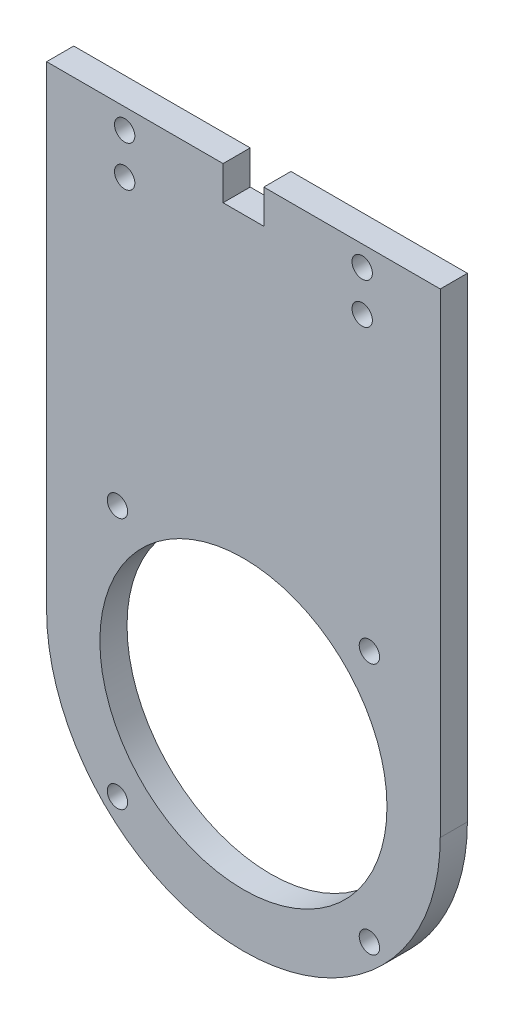
SolidWorks part; units mm, degrees
ref_plane "前视基准面" through (0, 0, 0) normal (0, 0, 1) x (1, 0, 0)
ref_plane "上视基准面" through (0, 0, 0) normal (0, 1, 0) x (1, 0, 0)
ref_plane "右视基准面" through (0, 0, 0) normal (1, 0, 0) x (0, 0, -1)
other "Configuration Table"
sketch "草图1" plane through (0, 0, 0) normal (0, 0, 1) x (1, 0, 0)
  line L0 (-29, 6) -> (29, 6)
  line L1 (29, 6) -> (29, -64)
  line L2 (0, 0) -> (0, 6) construction
  line L3 (-29, 6) -> (-29, -64)
  line L4 (-29, -64) -> (29, -64) construction
  line L5 (0, 3) -> (-17.5, 3) construction
  line L6 (0, -64) -> (18.5616, -82.5616) construction
  line L7 (-17.5, 3) -> (-17.5, -3) construction
  arc A0 (-29, -64) -> (29, -64) centre (0, -64) ccw
  circle A1 centre (0, -64) radius 21.15
  circle A2 centre (-17.5, 3) radius 1.5
  circle A3 centre (17.5, 3) radius 1.5
  circle A4 centre (0, -64) radius 54 construction
  circle A5 centre (18.5616, -82.5616) radius 1.5
  circle A6 centre (-18.5616, -82.5616) radius 1.5
  circle A7 centre (-18.5616, -45.4384) radius 1.5
  circle A8 centre (18.5616, -45.4384) radius 1.5
  circle A9 centre (-17.5, -3) radius 1.5
  circle A10 centre (17.5, -3) radius 1.5
  point P27 (0, -64)
  dimension "D1" = 42.3
  dimension "D4" = 35
  dimension "D5" = 3
  dimension "D6" = 108
  dimension "D8" = 3
  dimension "D10" = 26.25
  dimension "D2" = 6
  dimension "D3" = 58
  dimension "D7" = 70
  dimension "D9" = 45
  dimension "D13" = 6
  dimension "D12" = 2
  dimension "D11" = 4
extrude "凸台-拉伸1" add sketch "草图1" along normal blind 4 contours L3 A0 L1 L0 A1 A2 A3
sketch "草图2" plane through (0, 0, 4) normal (0, 0, 1) x (1, 0, 0)
  line L0 (-29, 6) -> (29, 6) construction
  line L1 (-3, 6) -> (3, 6)
  line L2 (-3, 6) -> (-3, 1)
  line L3 (-3, 1) -> (3, 1)
  line L4 (3, 6) -> (3, 1)
  line L5 (0, 0) -> (0, 6) construction
  dimension "D1" = 6
  dimension "D2" = 5
extrude "切除-拉伸1" cut sketch "草图2" against normal through all
